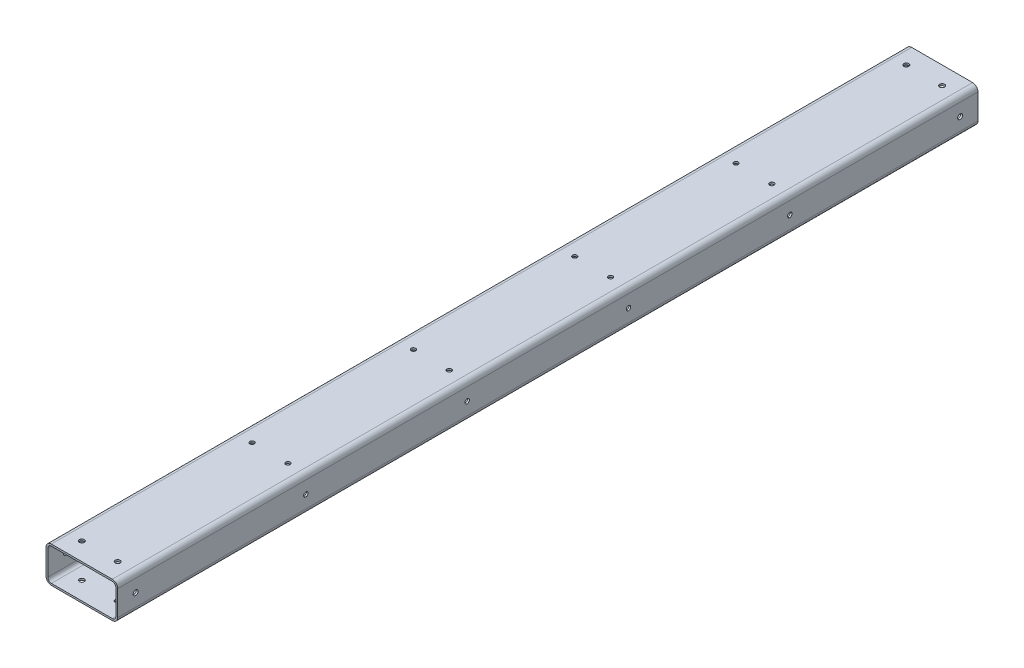
SolidWorks part; units mm, degrees
material "1.0038 (S235JRG2)"
ref_plane "Ebene vorne" through (0, 0, 0) normal (0, 0, 1) x (1, 0, 0)
ref_plane "Ebene oben" through (0, 0, 0) normal (0, 1, 0) x (1, 0, 0)
ref_plane "Ebene rechts" through (0, 0, 0) normal (1, 0, 0) x (0, 0, -1)
sketch "Skizze1" plane through (0, 0, 0) normal (0, 0, 1) x (1, 0, 0)
  line L0 (0, 0) -> (0, 67.8952) construction
  line L1 (-34, 20) -> (34, 20)
  line L2 (0, 0) -> (65.406, 0) construction
  line L3 (40, 14) -> (40, -14)
  line L4 (-40, 14) -> (-40, -14)
  line L5 (-34, -20) -> (34, -20)
  line L6 (-38, 14) -> (-38, -14)
  line L7 (-34, -18) -> (34, -18)
  line L8 (38, 14) -> (38, -14)
  line L9 (-34, 18) -> (34, 18)
  arc A0 (34, 20) -> (40, 14) centre (34, 14) cw
  arc A1 (-34, 20) -> (-40, 14) centre (-34, 14) ccw
  arc A2 (-34, -20) -> (-40, -14) centre (-34, -14) cw
  arc A3 (34, -20) -> (40, -14) centre (34, -14) ccw
  arc A4 (-34, -18) -> (-38, -14) centre (-34, -14) cw
  arc A5 (34, -18) -> (38, -14) centre (34, -14) ccw
  arc A6 (34, 18) -> (38, 14) centre (34, 14) cw
  arc A7 (-34, 18) -> (-38, 14) centre (-34, 14) ccw
  point P12 (40, 0)
  point P13 (0, 20)
  point P19 (-40, 0)
  dimension "D1" = 6
  dimension "D3" = 80
  dimension "D4" = 40
  dimension "D2" = 2
extrude "Aufsatz-Linear austragen1" add sketch "Skizze1" along normal mid plane 960
sketch "Skizze2" plane through (0, 20, 0) normal (0, 1, 0) x (1, 0, 0)
  line L0 (0, 0) -> (158.9829, 0) construction
  line L1 (0, 0) -> (0, 511.1822) construction
  line L2 (34, 480) -> (-34, 480) construction
  line L3 (40, -480) -> (40, 480) construction
  line L4 (20, 460) -> (-20, 460) construction
  line L5 (-40, -480) -> (-40, 480) construction
  circle A0 centre (20, 460) radius 2.75
  circle A1 centre (-20, 460) radius 2.75
  circle A2 centre (20, -460) radius 2.75
  circle A3 centre (-20, -460) radius 2.75
  point P18 (-20, -460)
  dimension "D1" = 5.5
  dimension "D2" = 20
  dimension "D3" = 20
  dimension "D4" = 20
extrude "Schnitt-Linear austragen1" cut sketch "Skizze2" against normal blind 100
sketch "Skizze3" plane through (40, 0, 0) normal (1, 0, 0) x (0, 0, -1)
  line L0 (0, 0) -> (503.9557, 0) construction
  line L1 (0, 0) -> (0, 132.2659) construction
  line L2 (480, -14) -> (480, 14) construction
  circle A0 centre (460, 0) radius 2.75
  circle A1 centre (-460, 0) radius 2.75
  dimension "D1" = 20
  dimension "D2" = 5.5
extrude "Schnitt-Linear austragen2" cut sketch "Skizze3" against normal blind 100
sketch "Skizze4" plane through (40, 0, 0) normal (1, 0, 0) x (0, 0, -1)
  line L0 (0, 0) -> (-521.89, 0) construction
  line L1 (0, 0) -> (0, 113.4349) construction
  line L2 (-480, -14) -> (-480, 14) construction
  circle A0 centre (-270, 0) radius 2.5
  circle A1 centre (-90, 0) radius 2.5
  circle A5 centre (90, 0) radius 2.5
  circle A6 centre (270, 0) radius 2.5
  dimension "D1" = 210
  dimension "D2" = 180
  dimension "D4" = 5
extrude "Schnitt-Linear austragen3" cut sketch "Skizze4" against normal blind 100
sketch "Skizze5" plane through (0, 20, 0) normal (0, 1, 0) x (1, 0, 0)
  line L0 (0, 0) -> (0, 503.059) construction
  line L1 (20, 270) -> (20, 90) construction
  line L2 (34, 480) -> (-34, 480) construction
  line L3 (0, 0) -> (298.2379, 0) construction
  line L4 (40, -480) -> (40, 480) construction
  line L6 (-20, 270) -> (-20, 90) construction
  line L7 (-40, -480) -> (-40, 480) construction
  line L8 (20, 270) -> (-20, 270) construction
  line L9 (-20, 90) -> (20, 90) construction
  circle A0 centre (20, 270) radius 2.5
  circle A1 centre (20, 90) radius 2.5
  circle A2 centre (-20, 90) radius 2.5
  circle A3 centre (-20, 270) radius 2.5
  circle A4 centre (20, -90) radius 2.5
  circle A5 centre (-20, -90) radius 2.5
  circle A6 centre (20, -270) radius 2.5
  circle A7 centre (-20, -270) radius 2.5
  dimension "D1" = 210
  dimension "D3" = 5
  dimension "D5" = 20
  dimension "D2" = 180
  dimension "D4" = 20
extrude "Schnitt-Linear austragen4" cut sketch "Skizze5" against normal blind 100
